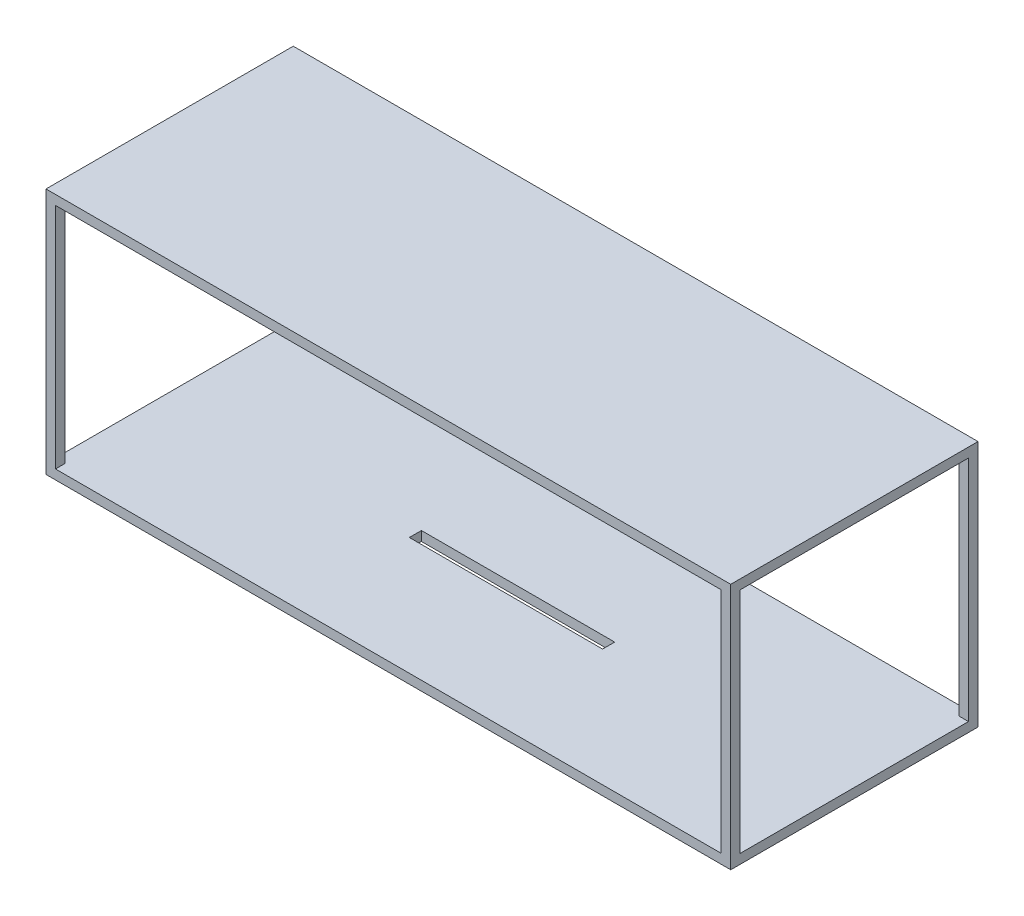
SolidWorks part; units mm, degrees
ref_plane "Front Plane" through (0, 0, 0) normal (0, 0, 1) x (1, 0, 0)
ref_plane "Top Plane" through (0, 0, 0) normal (0, 1, 0) x (1, 0, 0)
ref_plane "Right Plane" through (0, 0, 0) normal (1, 0, 0) x (0, 0, -1)
sketch "Sketch1" plane through (0, 0, 0) normal (0, 0, 1) x (1, 0, 0)
  line L1 (-180, 65) -> (180, 65)
  line L2 (-180, 65) -> (-180, -65)
  line L3 (-180, -65) -> (180, -65)
  line L4 (180, 65) -> (180, -65)
  line L5 (-180, 65) -> (180, -65) construction
  line L6 (-180, -65) -> (180, 65) construction
  point P0 (0, 0)
  dimension "D1" = 360
  dimension "D2" = 130
extrude "Boss-Extrude1" add sketch "Sketch1" along normal blind 130
shell "Shell1" thickness 5
sketch "Sketch2" plane through (0, 0, 130) normal (0, 0, 1) x (1, 0, 0)
  line L0 (180, 65) -> (-180, 65) construction
  line L1 (-175, 60) -> (175, 60)
  line L2 (-175, 60) -> (-175, -60)
  line L3 (-175, -60) -> (175, -60)
  line L4 (175, 60) -> (175, -60)
  line L5 (-175, 60) -> (175, -60) construction
  line L6 (-175, -60) -> (175, 60) construction
  line L7 (-180, 65) -> (-180, -65) construction
  point P0 (0, 0)
  dimension "D1" = 5
  dimension "D2" = 5
extrude "Cut-Extrude1" cut sketch "Sketch2" against normal through all
sketch "Sketch3" plane through (0, -60, 0) normal (0, 1, 0) x (1, 0, 0)
  line L0 (-180, -65) -> (180, -65) construction
  line L1 (-180, -130) -> (-180, 0) construction
  line L2 (180, -130) -> (180, 0) construction
  line L3 (0, 0) -> (0, -130) construction
  line L4 (180, -130) -> (-180, -130) construction
  line L6 (-50.8, -61.825) -> (50.8, -61.825)
  line L7 (-50.8, -61.825) -> (-50.8, -68.175)
  line L8 (-50.8, -68.175) -> (50.8, -68.175)
  line L9 (50.8, -61.825) -> (50.8, -68.175)
  line L10 (-50.8, -61.825) -> (50.8, -68.175) construction
  line L11 (-50.8, -68.175) -> (50.8, -61.825) construction
  point P11 (0, -65)
  dimension "D1" = 6.35
  dimension "D2" = 101.6
extrude "Cut-Extrude2" cut sketch "Sketch3" against normal through all
